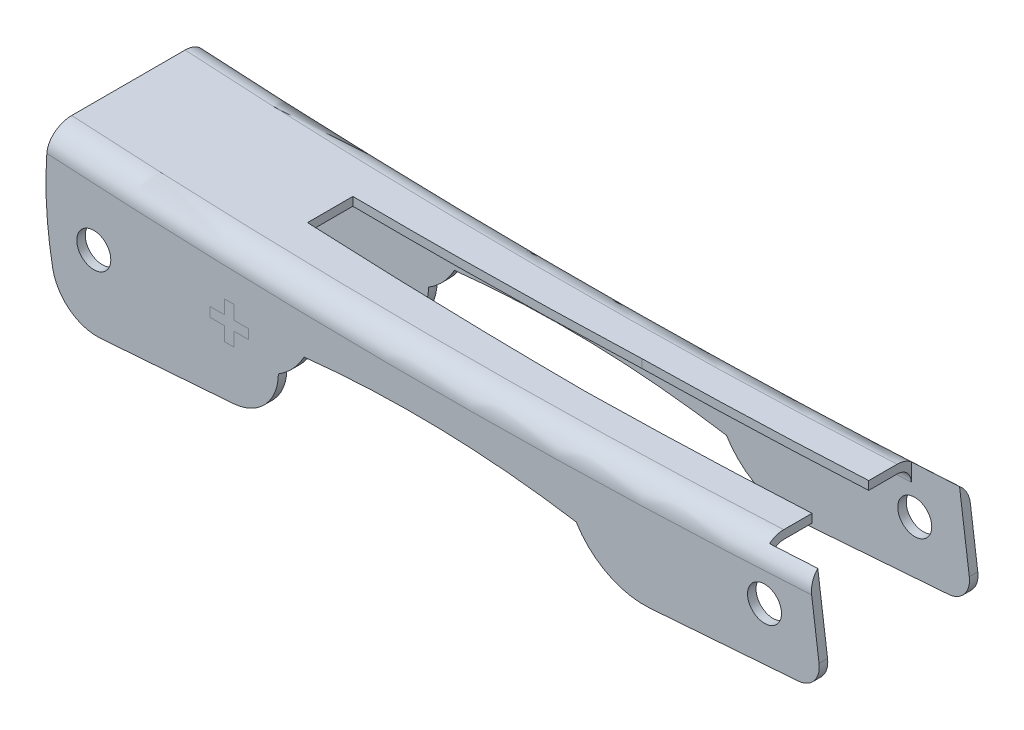
SolidWorks part; units mm, degrees
ref_plane "Front Plane" through (0, 0, 0) normal (0, 0, 1) x (1, 0, 0)
ref_plane "Top Plane" through (0, 0, 0) normal (0, 1, 0) x (1, 0, 0)
ref_plane "Right Plane" through (0, 0, 0) normal (1, 0, 0) x (0, 0, -1)
sketch "Sketch2" plane through (0, 0, 0) normal (0, 0, 1) x (1, 0, 0)
  line L0 (0, 0) -> (67, 0)
  line L1 (67, 0) -> (68.2, -9)
  line L2 (68.2, -9) -> (1.2, -14)
  line L3 (1.2, -14) -> (0, 0)
  arc A0 (67, 0) -> (0, 0) centre (33.5, 560.625) cw
  arc A1 (1.2, -14) -> (0, 0) centre (33.0128, -4.2218) cw
  point P7 (33.5, -1)
  point P8 (-0.1473, -7.0641)
  dimension "D1" = 67
  dimension "D2" = 9
  dimension "D3" = 1.2
  dimension "D4" = 1.2
  dimension "D5" = 14
  dimension "D6" = 1
  dimension "D7" = 0.75
extrude "Boss-Extrude1" add sketch "Sketch2" along normal mid plane 14 contours L1 A0 L3 L2 | A1 L3
fillet "Fillet1" radius 4 1 edges at (1.2, -14, 0)
fillet "Fillet2" radius 2 3 edges at (68.2, -9, 0) (33.5, -1, -7) (33.5, -1, 7)
shell "Shell1" thickness 0.75
sketch "Sketch4" plane through (0, 0, 0) normal (0, 1, 0) x (1, 0, 0)
  line L0 (0, 0) -> (69.3934, 0) construction
  line L1 (17.8, -2) -> (17.8, 2)
  line L2 (62.8, 2.5) -> (42.8, 2.5)
  line L3 (62.8, 2.5) -> (62.8, 6.25)
  line L4 (62.8, 6.25) -> (67.8, 6.25)
  line L5 (67.265, 6.25) -> (67.9199, 6.25) construction
  line L6 (67.8, 6.25) -> (67.8, -6.25)
  line L7 (42.8, 2.5) -> (17.8, 2)
  line L8 (67, -5) -> (67, 5) construction
  line L9 (42.8, -2.5) -> (17.8, -2)
  line L10 (62.8, -6.25) -> (67.8, -6.25)
  line L11 (62.8, -2.5) -> (62.8, -6.25)
  line L12 (62.8, -2.5) -> (42.8, -2.5)
  point P15 (17.8, 0)
  point P16 (67.8, 0)
  dimension "D1" = 2
  dimension "D2" = 0.8
  dimension "D3" = 5
  dimension "D4" = 25
  dimension "D5" = 50
  dimension "D6" = 3.75
extrude "Cut-Extrude1" cut sketch "Sketch4" against normal blind 14
sketch "Sketch5" plane through (0, 0, 7) normal (0, 0, 1) x (1, 0, 0)
  circle A0 centre (3.95, -7.3) radius 1.5
  circle A1 centre (63.1081, -4.7361) radius 1.5
  dimension "D1" = 3
  dimension "D2" = 3.95
  dimension "D3" = 7.3
  dimension "D4" = 4.3
  dimension "D5" = 3.95
extrude "Cut-Extrude2" cut sketch "Sketch5" against normal through all
sketch "Sketch6" plane through (0, 0, 7) normal (0, 0, 1) x (1, 0, 0)
  line L0 (16.25, -12.8769) -> (53, -10.1343)
  line L1 (66.0862, -9.1577) -> (4.5574, -13.7494) construction
  line L2 (16.25, -12.8769) -> (22.5, -6.2) construction
  arc A0 (53, -10.1343) -> (46.5, -6.8) centre (52.4786, -3.1479) cw
  arc A1 (46.5, -6.8) -> (22.5, -6.2) centre (32.2708, -95.668) ccw
  arc A4 (16.25, -12.8769) -> (20.2298, -8.6252) centre (15.93, -8.5888) ccw
  arc A5 (22.5, -6.2) -> (20.2298, -8.6252) centre (16.8526, -3.1888) cw
  dimension "D5" = 4.3
  dimension "D6" = 6.4
  dimension "D9" = 90
  dimension "D1" = 16.25
  dimension "D2" = 22.5
  dimension "D3" = 46.5
  dimension "D4" = 53
  dimension "D7" = 6.2
  dimension "D8" = 6.8
extrude "Cut-Extrude3" cut sketch "Sketch6" against normal through all
sketch "Sketch7" plane through (0, 0, 7) normal (0, 0, 1) x (1, 0, 0)
  text T0 "+" font "Century Gothic" height 5
split line "Split Line1"
